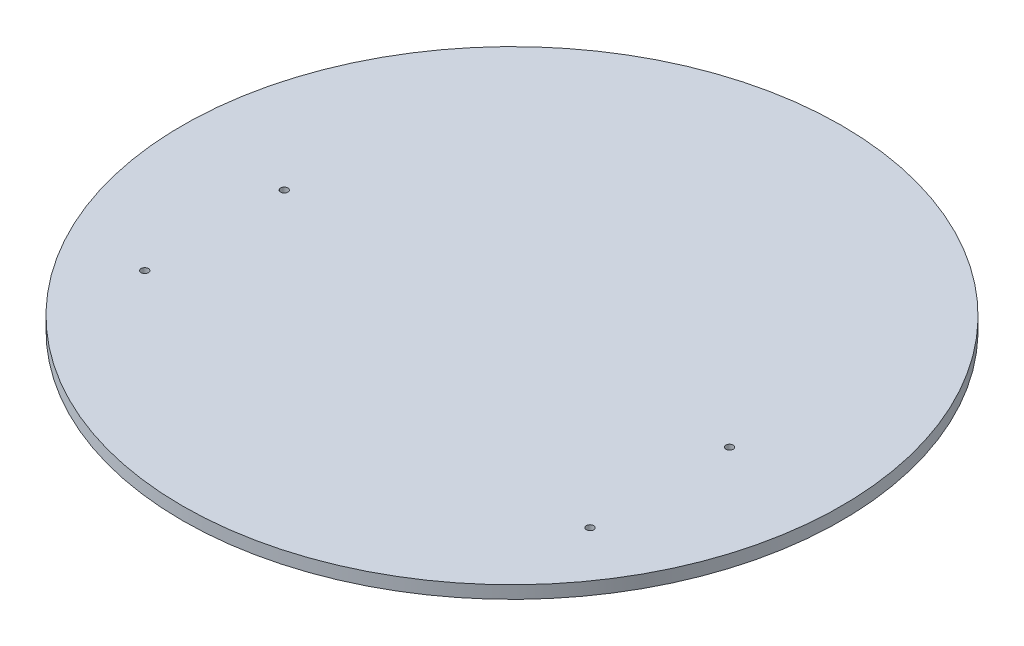
SolidWorks part; units mm, degrees
material "ABS"
ref_plane "Front Plane" through (0, 0, 0) normal (0, 0, 1) x (1, 0, 0)
ref_plane "Top Plane" through (0, 0, 0) normal (0, 1, 0) x (1, 0, 0)
ref_plane "Right Plane" through (0, 0, 0) normal (1, 0, 0) x (0, 0, -1)
sketch "Sketch1" plane through (0, 0, 0) normal (0, 1, 0) x (1, 0, 0)
  circle A0 centre (0, 0) radius 164.975
  dimension "D1" = 329.95
extrude "Boss-Extrude1" add sketch "Sketch1" along normal blind 6.35
ref_point "Point1"
hole_wizard "#6 Clearance Hole1" positions "3DSketch1" profile "Sketch2" hole size "#6" standard "Ansi Inch" end condition through all
sketch3d "3DSketch1"
  line L0 (0, 0, 0) -> (213.1626, 0, 0) construction
  line L2 (0, 0, 0) -> (0, 0, 209.6006) construction
  point P20 (111.465, 0, 2.54)
  point P22 (111.465, 0, 72.39)
  point P26 (111.465, 0, 2.54)
  point P28 (-111.465, 0, 72.39)
  point P29 (-111.465, 0, 2.54)
  dimension "D1" = 2.54
  dimension "D2" = 111.465
  dimension "D3" = 111.465
  dimension "D4" = 69.85
  dimension "D5" = 111.465
  dimension "D6" = 2.54
  dimension "D7" = 69.85
  dimension "D8" = 111.465
sketch "Sketch2" plane through (111.465, 0, 2.54) normal (1, 0, 0) x (0, 0, -1)
  line L0 (0, 0) -> (0, 6.35)
  line L1 (0, 6.35) -> (1.8288, 6.35)
  line L2 (1.8288, 6.35) -> (1.8288, 0)
  line L5 (1.8288, 0) -> (0, 0)
  line L11 (0, -6.35) -> (0, 107.95) construction
  dimension "Thru Hole Dia." = 3.6576
  dimension "Thru Hole Depth" = 6.35
